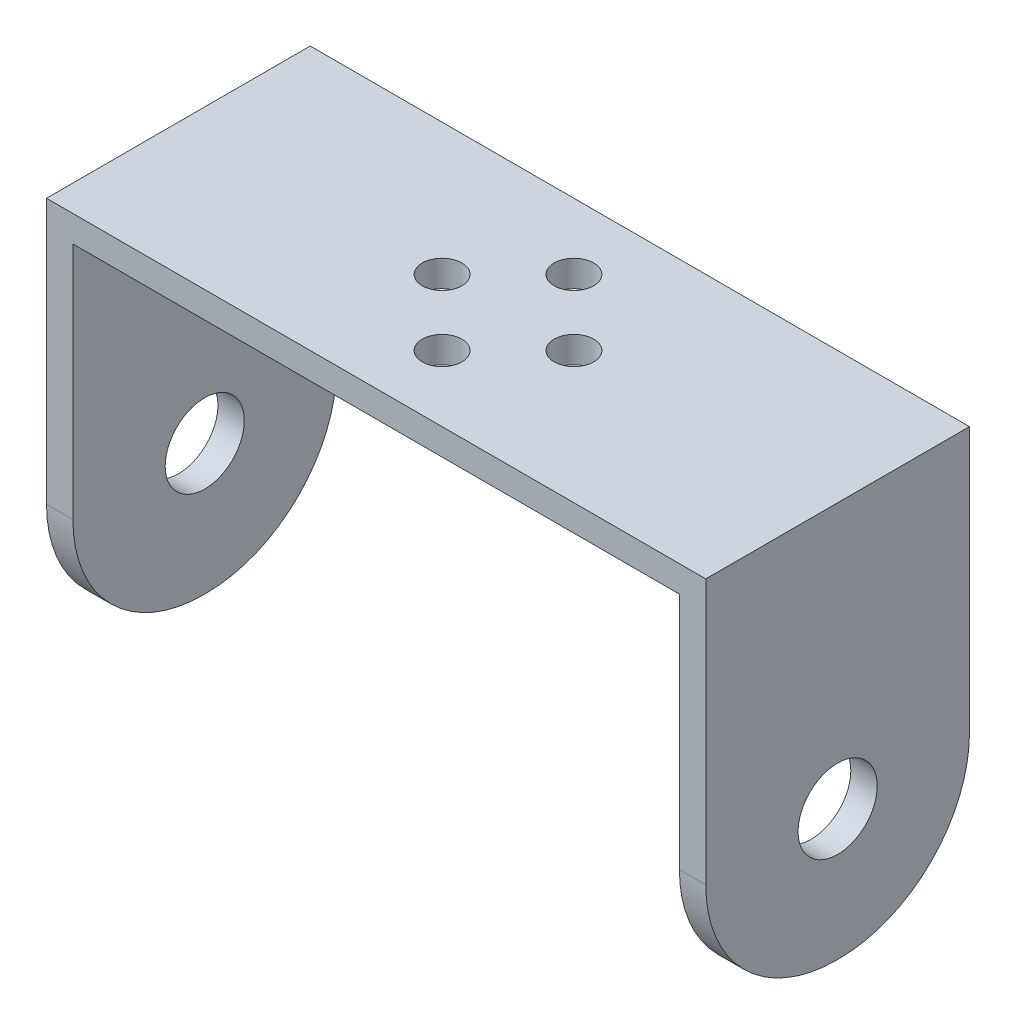
SolidWorks part; units mm, degrees
ref_plane "前视基准面" through (0, 0, 0) normal (0, 0, 1) x (1, 0, 0)
ref_plane "上视基准面" through (0, 0, 0) normal (0, 1, 0) x (1, 0, 0)
ref_plane "右视基准面" through (0, 0, 0) normal (1, 0, 0) x (0, 0, -1)
sketch "草图1" plane through (0, 0, 0) normal (0, 1, 0) x (1, 0, 0)
  line L1 (25, -10) -> (-25, -10)
  line L2 (25, -10) -> (25, 10)
  line L3 (25, 10) -> (-25, 10)
  line L4 (-25, -10) -> (-25, 10)
  line L5 (25, -10) -> (-25, 10) construction
  line L6 (25, 10) -> (-25, -10) construction
  point P0 (0, 0)
  dimension "D1" = 50
  dimension "D2" = 20
extrude "凸台-拉伸1" add sketch "草图1" along normal blind 2
sketch "草图2" plane through (-25, 0, 0) normal (-1, 0, 0) x (0, 0, 1)
  line L0 (-10, 2) -> (10, 2) construction
  line L1 (-10, 2) -> (10, 2)
  line L2 (-10, 2) -> (-10, -18.1)
  line L3 (-0.1, -28) -> (0.1, -28)
  line L4 (10, 2) -> (10, -18.1)
  line L5 (-10, 2) -> (-10, 0) construction
  arc A1 (-10, -18.1) -> (-0.1, -28) centre (-0.1, -18.1) ccw
  arc A2 (0.1, -28) -> (10, -18.1) centre (0.1, -18.1) ccw
  circle A3 centre (0, -18.1) radius 3
  point P9 (0, 0)
  point P10 (0, 0)
  point P18 (10, -28)
  dimension "D2" = 9.9
  dimension "D3" = 9.9
  dimension "D4" = 6
  dimension "D1" = 30
sketch "草图3" plane through (25, 0, 0) normal (1, 0, 0) x (0, 0, -1)
  line L0 (-10, 2) -> (10, 2)
  line L1 (-10, 2) -> (-10, -18.1)
  line L2 (-0.1, -28) -> (0.1, -28)
  line L3 (10, 2) -> (10, -18.1)
  line L4 (-10, 2) -> (-10, -18.1) construction
  arc A0 (-10, -18.1) -> (-0.1, -28) centre (-0.1, -18.1) ccw
  arc A1 (0.1, -28) -> (10, -18.1) centre (0.1, -18.1) ccw
  circle A2 centre (0, -18.1) radius 3
  point P8 (-13.549, 3.7417)
  point P9 (0, 0)
  point P10 (0, 0)
  point P11 (-13.4901, 5.8046)
  point P12 (0, 0)
  point P15 (0, 0)
  point P17 (0, 0)
  point P21 (0, 0)
  dimension "D1" = 9.9
  dimension "D2" = 9.9
  dimension "D3" = 6
extrude "凸台-拉伸2" add sketch "草图2" against normal blind 2
extrude "凸台-拉伸3" add sketch "草图3" against normal blind 2
sketch "草图4" plane through (0, 2, 0) normal (0, 1, 0) x (1, 0, 0)
  line L11 (-5, 5) -> (5, 5) construction
  line L12 (-5, 5) -> (-5, -5) construction
  line L13 (-5, -5) -> (5, -5) construction
  line L14 (5, 5) -> (5, -5) construction
  line L15 (-5, 5) -> (5, -5) construction
  line L16 (-5, -5) -> (5, 5) construction
  circle A0 centre (0, 5) radius 1.5
  circle A1 centre (5, 0) radius 1.5
  circle A2 centre (0, -5) radius 1.5
  circle A3 centre (-5, 0) radius 1.5
  point P0 (0, 0)
  point P14 (0, 0)
  point P15 (0, 0)
  dimension "D2" = 3
  dimension "D3" = 3
  dimension "D4" = 3
  dimension "D5" = 3
  dimension "D1" = 10
extrude "切除-拉伸1" cut sketch "草图4" against normal blind 2
